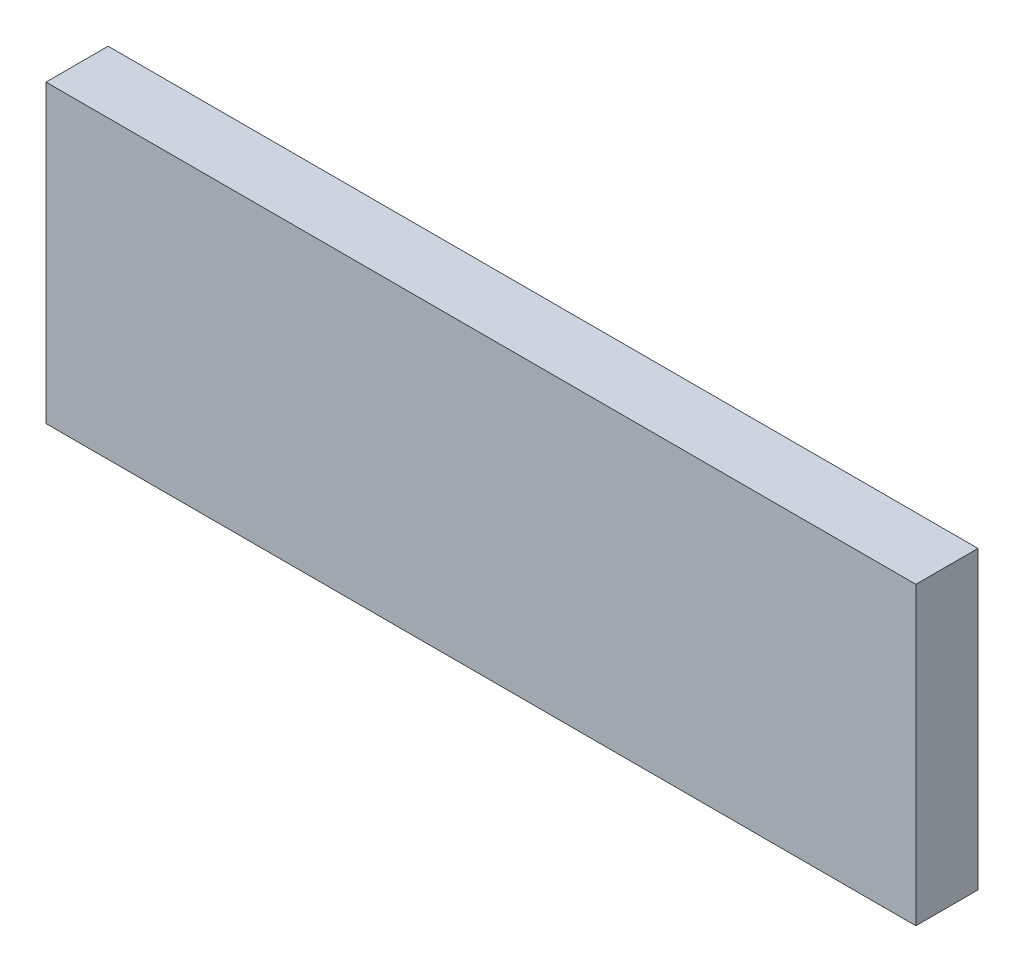
SolidWorks part; units mm, degrees
material "Alliage 1060"
ref_plane "Plan de face" through (0, 0, 0) normal (0, 0, 1) x (1, 0, 0)
ref_plane "Plan de dessus" through (0, 0, 0) normal (0, 1, 0) x (1, 0, 0)
ref_plane "Plan de droite" through (0, 0, 0) normal (1, 0, 0) x (0, 0, -1)
sketch "Esquisse1" plane through (0, 0, 0) normal (0, 0, 1) x (1, 0, 0)
  line L1 (-88.9, 30.226) -> (88.9, 30.226)
  line L2 (-88.9, 30.226) -> (-88.9, -30.226)
  line L3 (-88.9, -30.226) -> (88.9, -30.226)
  line L4 (88.9, 30.226) -> (88.9, -30.226)
  line L5 (-88.9, 30.226) -> (88.9, -30.226) construction
  line L6 (-88.9, -30.226) -> (88.9, 30.226) construction
  point P0 (0, 0)
  dimension "D1" = 177.8
  dimension "D2" = 60.452
extrude "Boss.-Extru.1" add sketch "Esquisse1" along normal blind 12.7
sketch "Esquisse2" plane through (0, 0, 12.7) normal (0, 0, 1) x (1, 0, 0)
  line L1 (88.9, -30.226) -> (88.9, 30.226) construction
  line L4 (88.9, 30.226) -> (-88.9, 30.226) construction
  line L5 (88.9, 0) -> (-88.9, 0) construction
  line L6 (-88.9, 30.226) -> (-88.9, -30.226) construction
  line L7 (0, 30.226) -> (0, -30.226) construction
  line L8 (-88.9, -30.226) -> (88.9, -30.226) construction
  circle A0 centre (79.375, 20.701) radius 3.175
  circle A1 centre (-79.375, 20.701) radius 3.175
  circle A2 centre (-79.375, -20.701) radius 3.175
  circle A3 centre (79.375, -20.701) radius 3.175
  dimension "D1" = 6.35
  dimension "D2" = 6.35
  dimension "D3" = 6.35
extrude "Enlèv. mat.-Extru.1" [suppressed] cut sketch "Esquisse2" against normal blind 12.7
